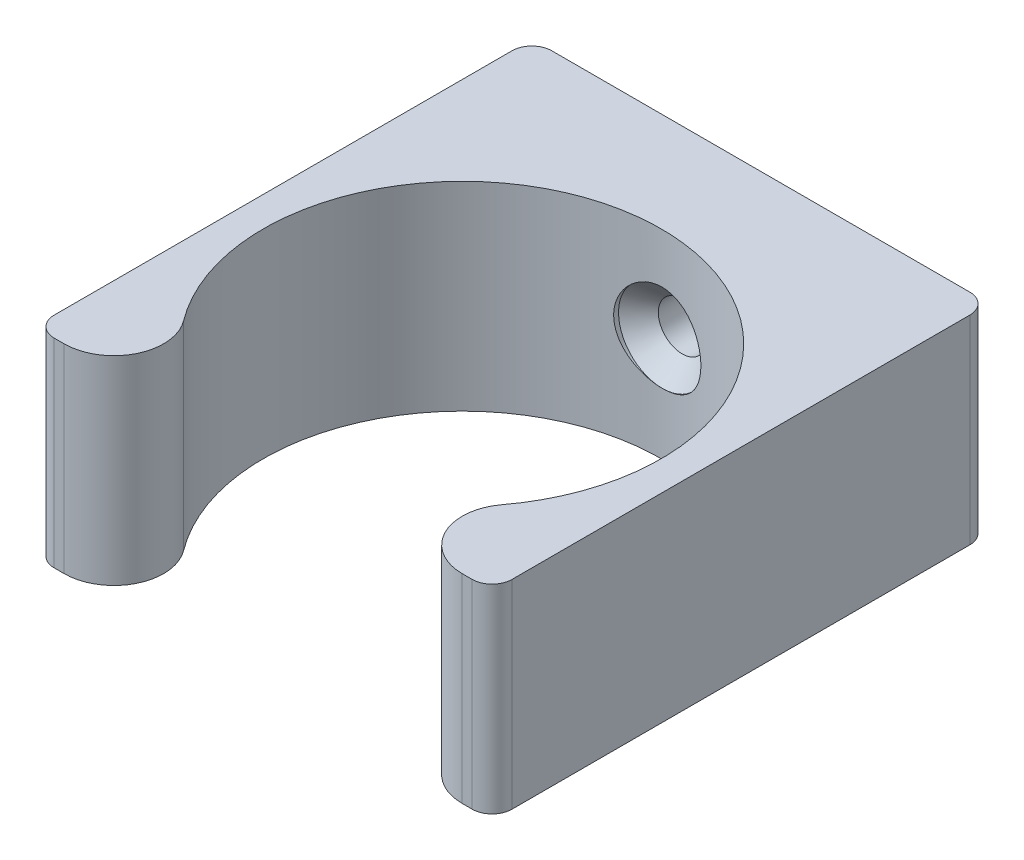
SolidWorks part; units mm, degrees
ref_plane "Front Plane" through (0, 0, 0) normal (0, 0, 1) x (1, 0, 0)
ref_plane "Top Plane" through (0, 0, 0) normal (0, 1, 0) x (1, 0, 0)
ref_plane "Right Plane" through (0, 0, 0) normal (1, 0, 0) x (0, 0, -1)
sketch "Sketch1" plane through (0, 0, 0) normal (0, 1, 0) x (1, 0, 0)
  line L1 (-10.5, -12.5) -> (-10, -12.5)
  line L2 (-11.5, -11.5) -> (-11.5, 11.5)
  line L3 (-10.5, 12.5) -> (10.5, 12.5)
  line L4 (11.5, -11.5) -> (11.5, 11.5)
  line L5 (10, -12.5) -> (10.5, -12.5)
  arc A1 (7.976, -8.5319) -> (-8, -8.5) centre (0, -2.5) ccw
  arc A2 (-10, -12.5) -> (-8, -8.5) centre (-10, -10) ccw
  arc A3 (10, -12.5) -> (7.976, -8.5319) centre (10, -9.9997) cw
  arc A4 (11.5, -11.5) -> (10.5, -12.5) centre (10.5, -11.5) cw
  arc A5 (-10.5, -12.5) -> (-11.5, -11.5) centre (-10.5, -11.5) cw
  arc A6 (-11.5, 11.5) -> (-10.5, 12.5) centre (-10.5, 11.5) cw
  arc A7 (11.5, 11.5) -> (10.5, 12.5) centre (10.5, 11.5) ccw
  point P0 (0, 0)
  point P5 (0, -2.5)
  point P15 (0, 0)
  point P16 (0, 0)
  point P17 (0, 0)
  point P20 (11.5, -12.5)
  point P25 (-11.5, 12.5)
  point P28 (11.5, 12.5)
  point P29 (7.9771, -8.5304)
  point P30 (0, 0)
  point P31 (-8, -8.5021)
  dimension "D3" = 1
  dimension "D1" = 23
  dimension "D2" = 25
extrude "Boss-Extrude1" add sketch "Sketch1" along normal blind 10
hole_wizard "CSK for M2 Flat Head Machine Screw1" positions "3DSketch3" profile "Sketch9" countersink size "M2" standard "ANSI Metric" end condition through all
sketch3d "3DSketch3"
  point P0 (0.0429, 5.2857, -7.4999)
sketch "Sketch9" plane through (0.0429, 5.2857, -7.4999) normal (0, 1, 0) x (1, 0, 0.0043)
  line L0 (0, 0) -> (0, 5.0492)
  line L1 (0, 5.0492) -> (1.2, 5.0492)
  line L2 (1.2, 5.0492) -> (1.2, 1)
  line L3 (1.2, 1) -> (2.2, 0)
  line L5 (2.2, 0) -> (0, 0)
  line L6 (-1.2, 1) -> (-2.2, 0) construction
  line L11 (0, -6.35) -> (0, 107.95) construction
  dimension "Thru Hole Dia." = 2.4
  dimension "Thru Hole Depth" = 5.0492
  dimension "Near C'Sink Dia." = 4.4
  dimension "Near C'Sink Angle" = 90
